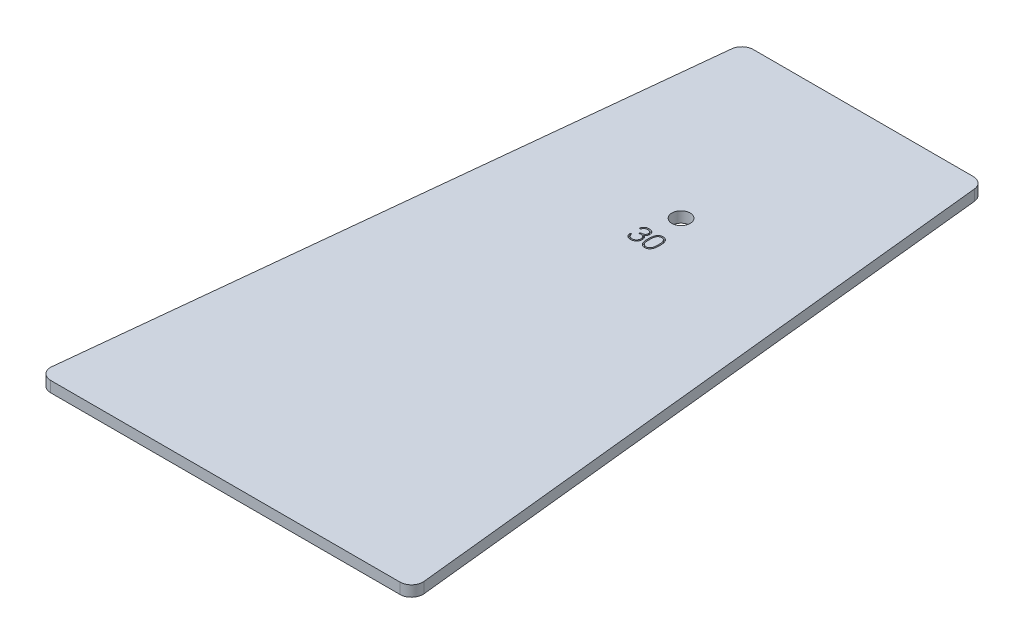
SolidWorks part; units mm, degrees
material "Acrylic (Medium-high impact)"
ref_plane "Front Plane" through (0, 0, 0) normal (0, 0, 1) x (1, 0, 0)
ref_plane "Top Plane" through (0, 0, 0) normal (0, 1, 0) x (1, 0, 0)
ref_plane "Right Plane" through (0, 0, 0) normal (1, 0, 0) x (0, 0, -1)
sketch "Sketch1" plane through (0, 0, 0) normal (0, 1, 0) x (1, 0, 0)
  line L0 (0, 0) -> (0, -355.6) construction
  line L1 (-67.056, 0) -> (67.056, 0)
  line L2 (67.056, 0) -> (104.4311, -355.6)
  line L3 (104.4311, -355.6) -> (-104.4311, -355.6)
  line L4 (-67.056, 0) -> (-104.4311, -355.6)
  dimension "D1" = 355.6
  dimension "D2" = 12
  dimension "D3" = 134.112
extrude "Boss-Extrude1" add sketch "Sketch1" along normal blind 5.9944
sketch "Sketch2" plane through (0, 5.9944, 0) normal (0, 1, 0) x (1, 0, 0)
  line L0 (0, 0) -> (0, -101.6) construction
  line L1 (67.056, 0) -> (-67.056, 0) construction
  circle A0 centre (0, -101.6) radius 5.08
  dimension "D2" = 10.16
  dimension "D1" = 101.6
extrude "Cut-Extrude1" cut sketch "Sketch2" against normal through all
sketch "Sketch3" plane through (0, 5.9944, 0) normal (0, 1, 0) x (1, 0, 0)
  line L0 (0, 0) -> (0, -114.3) construction
  line L1 (-7.62, -125.73) -> (7.62, -125.73) construction
  line L2 (-7.62, -125.73) -> (-7.62, -114.3) construction
  line L3 (-7.62, -114.3) -> (7.62, -114.3) construction
  line L4 (7.62, -125.73) -> (7.62, -114.3) construction
  line L5 (67.056, 0) -> (-67.056, 0) construction
  text T0 "30"
  dimension "D1" = 114.3
  dimension "D2" = 11.43
  dimension "D3" = 15.24
extrude "Cut-Extrude2" cut sketch "Sketch3" against normal blind 1.27
fillet "Fillet1" radius 6.35 4 edges at (104.4311, 2.9972, 355.6) (-104.4311, 2.9972, 355.6) (67.056, 2.9972, 0) (-67.056, 2.9972, 0)
move or copy body "Body-Move/Copy1" [suppressed] bodies to move or copy 103 copy no rotation origin (0, 0, 177.8) rotation axis (0, 1, 0) rotation angle 90
